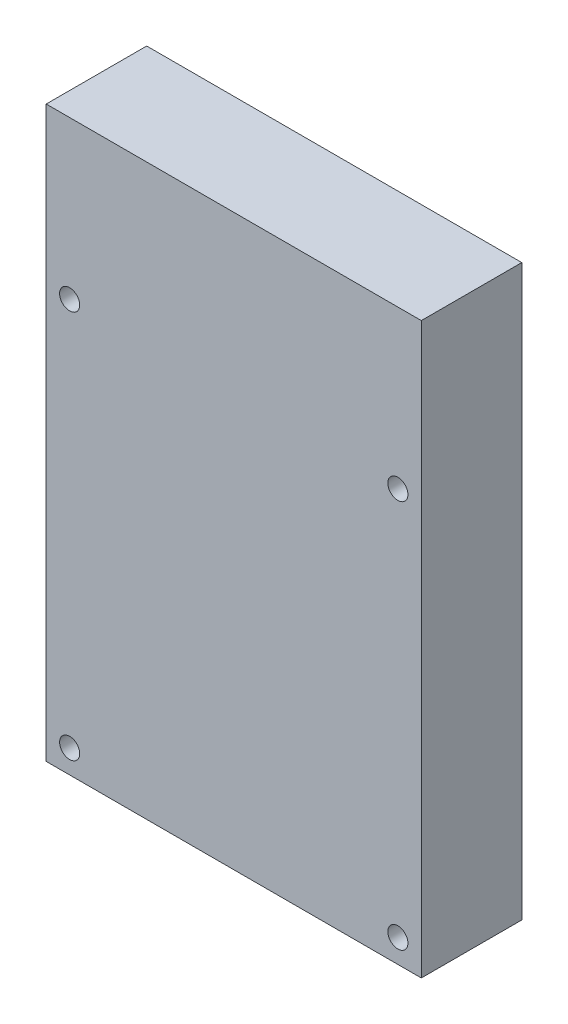
SolidWorks part; units mm, degrees
ref_plane "前视基准面" through (0, 0, 0) normal (0, 0, 1) x (1, 0, 0)
ref_plane "上视基准面" through (0, 0, 0) normal (0, 1, 0) x (1, 0, 0)
ref_plane "右视基准面" through (0, 0, 0) normal (1, 0, 0) x (0, 0, -1)
sketch "草图1" plane through (0, 0, 0) normal (0, 0, 1) x (1, 0, 0)
  line L0 (-9.6837, 50.8864) -> (-9.6837, -7.1136) construction
  line L1 (-9.6837, 50.8864) -> (39.3163, 50.8864) construction
  line L2 (39.3163, 50.8864) -> (39.3163, -7.1136) construction
  line L3 (-9.6837, -7.1136) -> (-13.1837, -7.1136)
  line L4 (-13.1837, 74.3864) -> (42.8163, 74.3864)
  line L5 (-13.1837, 74.3864) -> (-13.1837, -10.6136)
  line L6 (-13.1837, -10.6136) -> (42.8163, -10.6136)
  line L7 (42.8163, 74.3864) -> (42.8163, -10.6136)
  line L8 (39.3163, -7.1136) -> (42.8163, -7.1136) construction
  circle A0 centre (-9.6837, 50.8864) radius 1.5
  circle A1 centre (39.3163, 50.8864) radius 1.5
  circle A2 centre (-9.6837, -7.1136) radius 1.5
  circle A4 centre (39.3163, -7.1136) radius 1.5
  dimension "D1" = 3
  dimension "D2" = 58
  dimension "D3" = 49
  dimension "D4" = 85
  dimension "D5" = 56
  dimension "D6" = 3.5
extrude "凸台-拉伸1" add sketch "草图1" along normal blind 15
